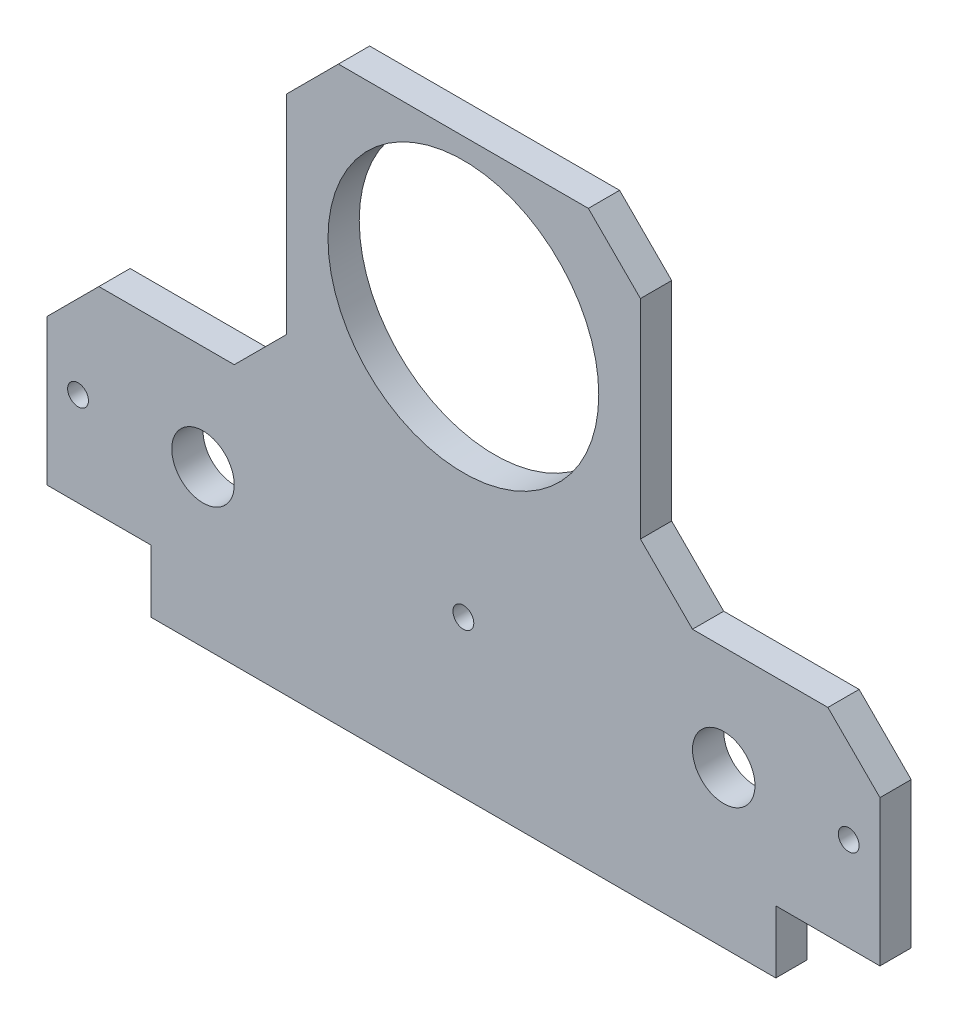
SolidWorks part; units mm, degrees
ref_plane "Plan de face" through (0, 0, 0) normal (0, 0, 1) x (1, 0, 0)
ref_plane "Plan de dessus" through (0, 0, 0) normal (0, 1, 0) x (1, 0, 0)
ref_plane "Plan de droite" through (0, 0, 0) normal (1, 0, 0) x (0, 0, -1)
sketch "Esquisse1" plane through (0, 0, 0) normal (0, 0, 1) x (1, 0, 0)
  line L0 (0, 0) -> (0, 55) construction
  line L1 (-40, 0) -> (40, 0)
  line L2 (40, 0) -> (40, 25)
  line L3 (40, 25) -> (17, 25)
  line L4 (17, 25) -> (17, 55)
  line L5 (17, 55) -> (-17, 55)
  line L6 (-17, 25) -> (-17, 55)
  line L7 (-40, 25) -> (-17, 25)
  line L8 (-40, 0) -> (-40, 25)
  line L9 (17, 40) -> (0, 40) construction
  circle A0 centre (0, 40) radius 13
  dimension "D4" = 26
  dimension "D5" = 40
  dimension "D1" = 80
  dimension "D2" = 34
  dimension "D3" = 30
extrude "Boss.-Extru.1" add sketch "Esquisse1" along normal blind 12
sketch "Esquisse2" plane through (0, 0, 12) normal (0, 0, 1) x (1, 0, 0)
  circle A0 centre (0, 40) radius 13
  circle A1 centre (0, 40) radius 5.5
  dimension "D1" = 26
  dimension "D2" = 11
extrude "Boss.-Extru.2" add sketch "Esquisse2" along normal blind 3 from vertex at -12 starting at point (17, 55, 0)
sketch "Esquisse4" plane through (0, 0, 0) normal (0, 0, -1) x (-1, 0, 0)
  line L0 (0, 0) -> (0, 55) construction
  line L1 (-17, 55) -> (17, 55) construction
  line L3 (40, 0) -> (-40, 0) construction
  line L4 (-40, 0) -> (-40, 25) construction
  circle A0 centre (-25, 15) radius 8
  circle A1 centre (25, 15) radius 8
  dimension "D1" = 16
  dimension "D2" = 15
  dimension "D3" = 15
extrude "Enlèv. mat.-Extru.2" cut sketch "Esquisse4" against normal blind 6
sketch "Esquisse5" plane through (0, 0, 6) normal (0, 0, -1) x (-1, 0, 0)
  line L0 (0, 0) -> (0, 55) construction
  line L1 (40, 0) -> (-40, 0) construction
  line L2 (-17, 55) -> (17, 55) construction
  circle A0 centre (-25, 15) radius 3
  circle A1 centre (25, 15) radius 3
  dimension "D1" = 6
extrude "Enlèv. mat.-Extru.3" cut sketch "Esquisse5" against normal through all
sketch "Esquisse6" plane through (0, 0, 12) normal (0, 0, 1) x (1, 0, 0)
  line L0 (0, 0) -> (0, 7.1495) construction
  line L1 (30, 0) -> (30, 6)
  line L2 (-40, 0) -> (-30, 0)
  line L3 (-40, 0) -> (-40, 6)
  line L4 (-40, 6) -> (-30, 6)
  line L5 (-30, 0) -> (-30, 6)
  line L6 (40, 6) -> (30, 6)
  line L7 (40, 0) -> (40, 6)
  line L8 (40, 0) -> (30, 0)
  dimension "D1" = 6
  dimension "D2" = 10
extrude "Enlèv. mat.-Extru.4" cut sketch "Esquisse6" against normal up to vertex
chamfer "Chanfrein1" distance 5 angle 45 6 edges at (40, 25, 6) (17, 25, 6) (-17, 25, 6) (-40, 25, 6) (17, 55, 6) (-17, 55, 6)
sketch "Esquisse7" plane through (0, 0, 0) normal (0, 0, -1) x (-1, 0, 0)
  line L0 (0, 0) -> (0, 55) construction
  line L1 (-12, 55) -> (12, 55) construction
  line L2 (0, 15) -> (-37, 15) construction
  line L3 (30, 0) -> (-30, 0) construction
  circle A0 centre (-10, 45) radius 1
  circle A1 centre (10, 45) radius 1
  circle A2 centre (-37, 15) radius 1
  circle A3 centre (37, 15) radius 1
  circle A4 centre (0, 15) radius 1
  dimension "D3" = 2
  dimension "D1" = 10
  dimension "D2" = 10
  dimension "D4" = 15
  dimension "D5" = 37
extrude "Enlèv. mat.-Extru.5" cut sketch "Esquisse7" against normal up to vertex (12 mm away) up to point (-35, 25, 12)
sketch "Esquisse8" plane through (0, 55, 0) normal (0, 1, 0) x (1, 0, 0)
  line L0 (40, 0) -> (40, -12) construction
  line L1 (-40, 0) -> (40, 0)
  line L2 (-40, 0) -> (-40, -9)
  line L3 (-40, -9) -> (40, -9)
  line L4 (40, 0) -> (40, -9)
  line L5 (40, -12) -> (35, -12) construction
  dimension "D1" = 3
extrude "Enlèv. mat.-Extru.6" cut sketch "Esquisse8" against normal through all
